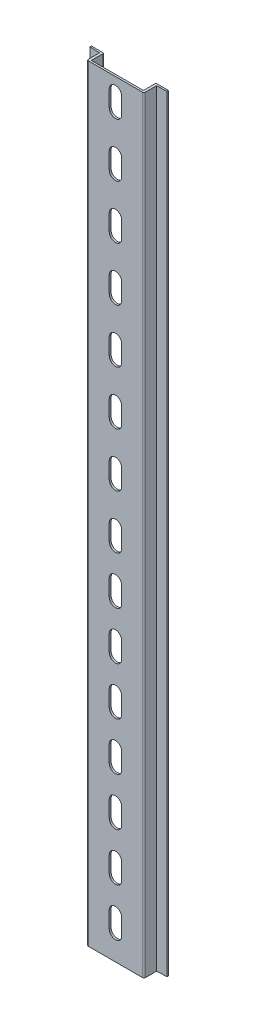
SolidWorks part; units mm, degrees
ref_plane "Alzado" through (0, 0, 0) normal (0, 0, 1) x (1, 0, 0)
ref_plane "Planta" through (0, 0, 0) normal (0, 1, 0) x (1, 0, 0)
ref_plane "Vista lateral" through (0, 0, 0) normal (1, 0, 0) x (0, 0, -1)
sketch "Croquis1" plane through (0, 0, 0) normal (0, 1, 0) x (1, 0, 0)
  line L0 (20.036, -8.0144) -> (20.036, 0) construction
  line L1 (34.92, -1.4884) -> (40.0721, -1.2268)
  line L3 (6.4521, -0.9884) -> (6.4521, -6.7144)
  line L4 (0, -0.4884) -> (5.9521, -0.4884)
  line L5 (5.8521, -8.0144) -> (34.22, -8.0144)
  line L6 (34.92, -1.4884) -> (34.92, -7.3144)
  line L8 (40.0721, -0.4884) -> (34.12, -0.4884)
  line L9 (33.62, -0.9884) -> (33.62, -6.7144)
  line L10 (5.1521, -1.4884) -> (5.1521, -7.3144)
  line L11 (6.7521, -7.0144) -> (33.32, -7.0144) construction
  line L12 (5.1521, -1.4884) -> (0, -1.2268)
  line L13 (6.7521, -7.0144) -> (33.32, -7.0144)
  arc A0 (34.22, -8.0144) -> (34.92, -7.3144) centre (34.22, -7.3144) ccw
  arc A1 (34.12, -0.4884) -> (33.62, -0.9884) centre (34.12, -0.9884) ccw
  arc A2 (33.32, -7.0144) -> (33.62, -6.7144) centre (33.32, -6.7144) ccw
  arc A3 (6.7521, -7.0144) -> (6.4521, -6.7144) centre (6.7521, -6.7144) cw
  arc A4 (5.9521, -0.4884) -> (6.4521, -0.9884) centre (5.9521, -0.9884) cw
  arc A5 (5.8521, -8.0144) -> (5.1521, -7.3144) centre (5.8521, -7.3144) cw
  spline S0 degree 2 poles (40.0721, -0.4884) (40.1909, -0.8585) (40.0721, -1.2268) knots 0 0 0 1 1 1
  spline S1 degree 2 poles (0, -0.4884) (-0.1188, -0.8585) (0, -1.2268) knots 0 0 0 1 1 1
extrude "Saliente-Extruir1" add sketch "Croquis1" along normal blind 400 and the other way blind 0.1
sketch "Croquis2" plane through (0, 0, 8.0144) normal (0, 0, 1) x (1, 0, 0)
  line L0 (20.036, -0.1) -> (20.036, 10) construction
  line L1 (5.8521, -0.1) -> (34.22, -0.1) construction
  line L2 (20.036, 25) -> (20.036, 35) construction
  line L3 (16.786, 38.25) -> (16.786, 46.75)
  line L4 (23.286, 38.25) -> (23.286, 46.75)
  line L5 (16.786, 13.25) -> (16.786, 21.75)
  line L6 (16.786, 63.25) -> (16.786, 71.75)
  line L7 (23.286, 13.25) -> (23.286, 21.75)
  line L8 (23.286, 63.25) -> (23.286, 71.75)
  line L9 (16.786, 88.25) -> (16.786, 96.75)
  line L10 (23.286, 88.25) -> (23.286, 96.75)
  line L11 (16.786, 113.25) -> (16.786, 121.75)
  line L12 (23.286, 113.25) -> (23.286, 121.75)
  line L13 (16.786, 138.25) -> (16.786, 146.75)
  line L14 (23.286, 138.25) -> (23.286, 146.75)
  line L15 (16.786, 163.25) -> (16.786, 171.75)
  line L16 (23.286, 163.25) -> (23.286, 171.75)
  line L17 (16.786, 188.25) -> (16.786, 196.75)
  line L18 (23.286, 188.25) -> (23.286, 196.75)
  line L19 (40.0721, 199.95) -> (0, 199.95) construction
  line L20 (40.0721, -0.1) -> (40.0721, 400) construction
  line L21 (0, -0.1) -> (0, 400) construction
  line L22 (16.786, 216.25) -> (16.786, 224.75)
  line L23 (23.286, 216.25) -> (23.286, 224.75)
  line L24 (16.786, 244.25) -> (16.786, 252.75)
  line L25 (23.286, 244.25) -> (23.286, 252.75)
  line L26 (16.786, 272.25) -> (16.786, 280.75)
  line L27 (23.286, 272.25) -> (23.286, 280.75)
  line L28 (16.786, 300.25) -> (16.786, 308.75)
  line L29 (23.286, 300.25) -> (23.286, 308.75)
  line L30 (16.786, 328.25) -> (16.786, 336.75)
  line L31 (23.286, 328.25) -> (23.286, 336.75)
  line L32 (16.786, 356.25) -> (16.786, 364.75)
  line L33 (23.286, 356.25) -> (23.286, 364.75)
  line L34 (16.786, 384.25) -> (16.786, 392.75)
  line L35 (23.286, 384.25) -> (23.286, 392.75)
  arc A0 (23.286, 21.75) -> (16.786, 21.75) centre (20.036, 21.75) ccw
  arc A1 (16.786, 13.25) -> (23.286, 13.25) centre (20.036, 13.25) ccw
  arc A2 (23.286, 46.75) -> (16.786, 46.75) centre (20.036, 46.75) ccw
  arc A3 (16.786, 38.25) -> (23.286, 38.25) centre (20.036, 38.25) ccw
  arc A4 (23.286, 71.75) -> (16.786, 71.75) centre (20.036, 71.75) ccw
  arc A5 (16.786, 63.25) -> (23.286, 63.25) centre (20.036, 63.25) ccw
  arc A6 (23.286, 96.75) -> (16.786, 96.75) centre (20.036, 96.75) ccw
  arc A7 (16.786, 88.25) -> (23.286, 88.25) centre (20.036, 88.25) ccw
  arc A8 (23.286, 121.75) -> (16.786, 121.75) centre (20.036, 121.75) ccw
  arc A9 (16.786, 113.25) -> (23.286, 113.25) centre (20.036, 113.25) ccw
  arc A10 (23.286, 146.75) -> (16.786, 146.75) centre (20.036, 146.75) ccw
  arc A11 (16.786, 138.25) -> (23.286, 138.25) centre (20.036, 138.25) ccw
  arc A12 (23.286, 171.75) -> (16.786, 171.75) centre (20.036, 171.75) ccw
  arc A13 (16.786, 163.25) -> (23.286, 163.25) centre (20.036, 163.25) ccw
  arc A14 (23.286, 196.75) -> (16.786, 196.75) centre (20.036, 196.75) ccw
  arc A15 (16.786, 188.25) -> (23.286, 188.25) centre (20.036, 188.25) ccw
  arc A16 (23.286, 224.75) -> (16.786, 224.75) centre (20.036, 224.75) ccw
  arc A17 (16.786, 216.25) -> (23.286, 216.25) centre (20.036, 216.25) ccw
  arc A18 (23.286, 252.75) -> (16.786, 252.75) centre (20.036, 252.75) ccw
  arc A19 (16.786, 244.25) -> (23.286, 244.25) centre (20.036, 244.25) ccw
  arc A20 (23.286, 280.75) -> (16.786, 280.75) centre (20.036, 280.75) ccw
  arc A21 (16.786, 272.25) -> (23.286, 272.25) centre (20.036, 272.25) ccw
  arc A22 (23.286, 308.75) -> (16.786, 308.75) centre (20.036, 308.75) ccw
  arc A23 (16.786, 300.25) -> (23.286, 300.25) centre (20.036, 300.25) ccw
  arc A24 (23.286, 336.75) -> (16.786, 336.75) centre (20.036, 336.75) ccw
  arc A25 (16.786, 328.25) -> (23.286, 328.25) centre (20.036, 328.25) ccw
  arc A26 (23.286, 364.75) -> (16.786, 364.75) centre (20.036, 364.75) ccw
  arc A27 (16.786, 356.25) -> (23.286, 356.25) centre (20.036, 356.25) ccw
  arc A28 (23.286, 392.75) -> (16.786, 392.75) centre (20.036, 392.75) ccw
  arc A29 (16.786, 384.25) -> (23.286, 384.25) centre (20.036, 384.25) ccw
  dimension "D1" = 8
  dimension "D2" = 8
extrude "Cortar-Extruir4" cut sketch "Croquis2" against normal blind 10
sketch "Croquis4" plane through (0, 0, 7.0144) normal (0, 0, -1) x (-1, 0, 0)
  line L0 (-20.036, 10) -> (-20.036, -0.1) construction
  line L2 (-20.111, 24.95) -> (-19.961, 24.95)
  line L3 (-20.111, -0.05) -> (-19.961, -0.05)
  line L4 (-20.111, -0.05) -> (-20.111, 9.95)
  line L5 (-20.111, 9.95) -> (-19.961, 9.95)
  line L6 (-19.961, -0.05) -> (-19.961, 9.95)
  line L7 (-20.111, -0.05) -> (-19.961, 9.95) construction
  line L8 (-20.111, 9.95) -> (-19.961, -0.05) construction
  line L9 (-20.111, 24.95) -> (-20.111, 34.95)
  line L10 (-20.111, 34.95) -> (-19.961, 34.95)
  line L11 (-19.961, 24.95) -> (-19.961, 34.95)
  line L12 (-20.036, 35) -> (-20.036, 24.9) construction
  line L13 (-20.111, 24.95) -> (-19.961, 34.95) construction
  line L14 (-20.111, 34.95) -> (-19.961, 24.95) construction
  line L15 (-20.111, 49.95) -> (-19.961, 49.95)
  line L16 (-20.111, 49.95) -> (-20.111, 59.95)
  line L17 (-20.111, 59.95) -> (-19.961, 59.95)
  line L18 (-19.961, 49.95) -> (-19.961, 59.95)
  line L19 (-20.036, 60) -> (-20.036, 49.9) construction
  line L20 (-20.111, 49.95) -> (-19.961, 59.95) construction
  line L21 (-20.111, 59.95) -> (-19.961, 49.95) construction
  line L22 (-20.111, 74.95) -> (-19.961, 74.95)
  line L23 (-20.111, 74.95) -> (-20.111, 84.95)
  line L24 (-20.111, 84.95) -> (-19.961, 84.95)
  line L25 (-19.961, 74.95) -> (-19.961, 84.95)
  line L26 (-20.036, 85) -> (-20.036, 74.9) construction
  line L27 (-20.111, 74.95) -> (-19.961, 84.95) construction
  line L28 (-20.111, 84.95) -> (-19.961, 74.95) construction
  line L29 (-20.111, 99.95) -> (-19.961, 99.95)
  line L30 (-20.111, 99.95) -> (-20.111, 109.95)
  line L31 (-20.111, 109.95) -> (-19.961, 109.95)
  line L32 (-19.961, 99.95) -> (-19.961, 109.95)
  line L33 (-20.036, 110) -> (-20.036, 99.9) construction
  line L34 (-20.111, 99.95) -> (-19.961, 109.95) construction
  line L35 (-20.111, 109.95) -> (-19.961, 99.95) construction
  line L36 (-20.111, 124.95) -> (-19.961, 124.95)
  line L37 (-20.111, 124.95) -> (-20.111, 134.95)
  line L38 (-20.111, 134.95) -> (-19.961, 134.95)
  line L39 (-19.961, 124.95) -> (-19.961, 134.95)
  line L40 (-20.036, 135) -> (-20.036, 124.9) construction
  line L41 (-20.111, 124.95) -> (-19.961, 134.95) construction
  line L42 (-20.111, 134.95) -> (-19.961, 124.95) construction
  line L43 (-20.111, 149.95) -> (-19.961, 149.95)
  line L44 (-20.111, 149.95) -> (-20.111, 159.95)
  line L45 (-20.111, 159.95) -> (-19.961, 159.95)
  line L46 (-19.961, 149.95) -> (-19.961, 159.95)
  line L47 (-20.036, 160) -> (-20.036, 149.9) construction
  line L48 (-20.111, 149.95) -> (-19.961, 159.95) construction
  line L49 (-20.111, 159.95) -> (-19.961, 149.95) construction
  line L50 (-20.111, 174.95) -> (-19.961, 174.95)
  line L51 (-20.111, 174.95) -> (-20.111, 184.95)
  line L52 (-20.111, 184.95) -> (-19.961, 184.95)
  line L53 (-19.961, 174.95) -> (-19.961, 184.95)
  line L54 (-20.036, 185) -> (-20.036, 174.9) construction
  line L55 (-20.111, 174.95) -> (-19.961, 184.95) construction
  line L56 (-20.111, 184.95) -> (-19.961, 174.95) construction
  arc A0 (-23.286, 13.25) -> (-16.786, 13.25) centre (-20.036, 13.25) ccw construction
  point P6 (-20.036, 4.95)
  point P16 (-20.036, 29.95)
  point P23 (-20.036, 54.95)
  point P30 (-20.036, 79.95)
  point P37 (-20.036, 104.95)
  point P44 (-20.036, 129.95)
  point P51 (-20.036, 154.95)
  point P58 (-20.036, 179.95)
  dimension "D1" = 8
extrude "Cortar-Extruir9" cut sketch "Croquis4" against normal blind 0.1
